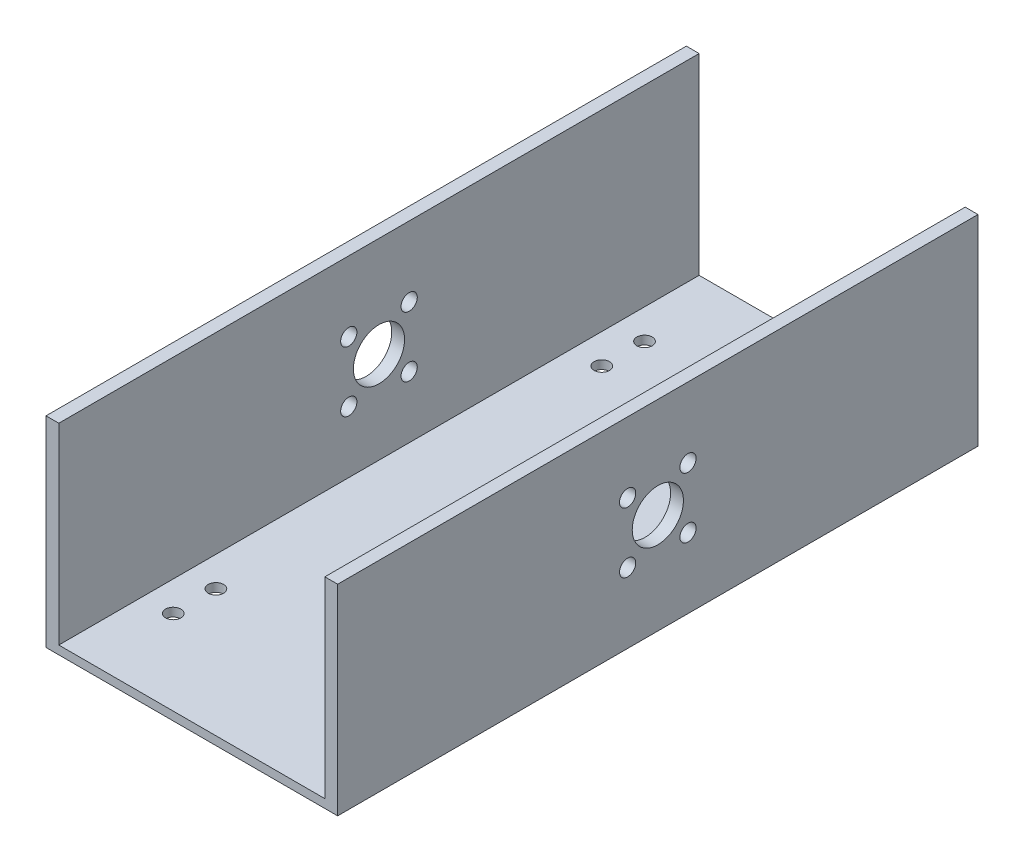
SolidWorks part; units mm, degrees
ref_plane "Alzado" through (0, 0, 0) normal (0, 0, 1) x (1, 0, 0)
ref_plane "Planta" through (0, 0, 0) normal (0, 1, 0) x (1, 0, 0)
ref_plane "Vista lateral" through (0, 0, 0) normal (1, 0, 0) x (0, 0, -1)
sketch "Croquis1" plane through (0, 0, 0) normal (0, 1, 0) x (1, 0, 0)
  line L0 (34.16, 45.2) -> (-34.16, 45.2) construction
  line L1 (34.16, 75) -> (-34.16, 75)
  line L2 (34.16, 75) -> (34.16, -75)
  line L3 (34.16, -75) -> (-34.16, -75)
  line L4 (-34.16, 75) -> (-34.16, -75)
  line L5 (34.16, 75) -> (-34.16, -75) construction
  line L6 (34.16, -75) -> (-34.16, 75) construction
  line L7 (34.16, 0) -> (-34.16, 0) construction
  line L8 (34.16, 55.2) -> (-34.16, 55.2) construction
  line L9 (24.16, 45.2) -> (24.16, 55.2) construction
  line L10 (-24.16, 45.2) -> (-24.16, 55.2) construction
  circle A0 centre (24.16, 45.2) radius 1.8
  circle A1 centre (24.16, 55.2) radius 1.8
  circle A2 centre (-24.16, -55.2) radius 1.8
  circle A3 centre (24.16, -55.2) radius 1.8
  circle A4 centre (-24.16, 45.2) radius 1.8
  circle A5 centre (-24.16, 55.2) radius 1.8
  circle A6 centre (-24.16, -45.2) radius 1.8
  circle A7 centre (24.16, -45.2) radius 1.8
  point P0 (0, 0)
  point P1 (0, 0)
  dimension "D3" = 48.32
  dimension "D4" = 3.6
  dimension "D5" = 19.8
  dimension "D1" = 150
  dimension "D2" = 10
  dimension "D6" = 10
  dimension "D7" = 10
extrude "Saliente-Extruir1" add sketch "Croquis1" along normal blind 2
sketch "Croquis2" plane through (0, 2, 0) normal (0, 1, 0) x (1, 0, 0)
  line L0 (-34.16, -75) -> (34.16, -75) construction
  line L1 (-34.16, 75) -> (-31.16, 75)
  line L2 (-34.16, 75) -> (-34.16, -75)
  line L3 (-34.16, -75) -> (-31.16, -75)
  line L4 (-31.16, 75) -> (-31.16, -75)
  dimension "D1" = 3
extrude "Saliente-Extruir2" add sketch "Croquis2" along normal blind 45
sketch "Croquis3" plane through (0, 2, 0) normal (0, 1, 0) x (1, 0, 0)
  line L0 (-31.16, -75) -> (34.16, -75) construction
  line L1 (34.16, 75) -> (31.16, 75)
  line L2 (34.16, 75) -> (34.16, -75)
  line L3 (34.16, -75) -> (31.16, -75)
  line L4 (31.16, 75) -> (31.16, -75)
  dimension "D1" = 3
extrude "Saliente-Extruir3" add sketch "Croquis3" along normal up to surface (45 mm away) up to face at (-32.66, 47, 0)
sketch "Croquis4" plane through (-34.16, 0, 0) normal (-1, 0, 0) x (0, 0, 1)
  line L0 (0, 47) -> (0, 0) construction
  line L1 (-75, 47) -> (75, 47) construction
  line L2 (-75, 0) -> (75, 0) construction
  line L3 (-75, 23.5) -> (75, 23.5) construction
  line L4 (-75, 47) -> (-75, 0) construction
  line L5 (75, 47) -> (75, 0) construction
  line L6 (7.0711, 30.5711) -> (0, 23.5) construction
  circle A0 centre (0, 23.5) radius 6
  circle A1 centre (0, 23.5) radius 10 construction
  circle A2 centre (7.0711, 30.5711) radius 1.9
  dimension "D1" = 3.8
  dimension "D2" = 20
  dimension "D3" = 12
  dimension "D4" = 45
extrude "Cortar-Extruir1" cut sketch "Croquis4" against normal through all
pattern_circular "MatrizC1" count 4 over 360 about axis through (0, 23.5, 0) along (1, 0, 0) of "Cortar-Extruir1"
